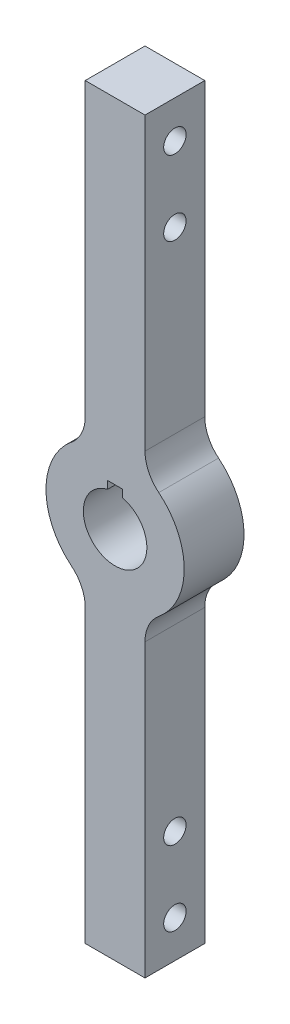
SolidWorks part; units mm, degrees
material "1060 Alloy"
ref_plane "Front Plane" through (0, 0, 0) normal (0, 0, 1) x (1, 0, 0)
ref_plane "Top Plane" through (0, 0, 0) normal (0, 1, 0) x (1, 0, 0)
ref_plane "Right Plane" through (0, 0, 0) normal (1, 0, 0) x (0, 0, -1)
sketch "Sketch1" plane through (0, 0, 0) normal (0, 0, 1) x (1, 0, 0)
  circle A0 centre (0, 0) radius 8.5
  circle A1 centre (0, 0) radius 18.5
  dimension "D1" = 17
  dimension "D2" = 37
extrude "Boss-Extrude1" add sketch "Sketch1" along normal mid plane 16
sketch "Sketch2" plane through (0, 0, 0) normal (0, 0, 1) x (1, 0, 0)
  line L0 (0, 0) -> (0, 40.1669) construction
  line L1 (-8, 100) -> (8, 100)
  line L2 (8, 100) -> (8, 16.6808)
  line L3 (8, 16.6808) -> (-8, 16.6808)
  line L4 (-8, 100) -> (-8, 16.6808)
  circle A0 centre (0, 0) radius 18.5 construction
  point P10 (0, 16.6808)
  point P11 (0, 100)
  dimension "D1" = 16
  dimension "D2" = 100
extrude "Boss-Extrude2" add sketch "Sketch2" along normal mid plane 16
sketch "Sketch3" plane through (0, 0, 0) normal (0, 0, 1) x (1, 0, 0)
  line L0 (0, 0) -> (0, -28.6568) construction
  line L1 (-8, -100) -> (8, -100)
  line L2 (8, -100) -> (8, -16.6808)
  line L3 (8, -16.6808) -> (-8, -16.6808)
  line L4 (-8, -100) -> (-8, -16.6808)
  arc A0 (-8, 16.6808) -> (8, 16.6808) centre (0, 0) ccw construction
  point P11 (0, -16.6808)
  point P12 (0, -100)
  dimension "D1" = 16
  dimension "D2" = 100
extrude "Boss-Extrude3" add sketch "Sketch3" along normal mid plane 16
sketch "Sketch4" plane through (0, 0, -8) normal (0, 0, -1) x (-1, 0, 0)
  line L0 (0, 0) -> (0, 24.3643) construction
  line L1 (2, 10.3) -> (-2, 10.3)
  line L2 (-2, 10.3) -> (-2, 8.2614)
  line L3 (-2, 8.2614) -> (2, 8.2614)
  line L4 (2, 10.3) -> (2, 8.2614)
  circle A0 centre (0, 0) radius 8.5 construction
  point P10 (0, 8.2614)
  point P11 (0, 10.3)
  dimension "D1" = 10.3
  dimension "D2" = 4
extrude "Cut-Extrude3" cut sketch "Sketch4" against normal through all
fillet "Fillet1" radius 10 4 edges at (8, -16.6808, 0) (-8, -16.6808, 0) (-8, 16.6808, 0) (8, 16.6808, 0)
sketch "Sketch5" plane through (8, 0, 0) normal (1, 0, 0) x (0, 0, -1)
  line L0 (0, 107.3318) -> (0, -108.104) construction
  line L1 (-8, 100) -> (8, 100) construction
  line L2 (-8, -100) -> (8, -100) construction
  circle A0 centre (0, 90) radius 3
  circle A1 centre (0, 70) radius 3
  circle A2 centre (0, -70) radius 3
  circle A3 centre (0, -90) radius 3
  dimension "D1" = 6
  dimension "D2" = 6
  dimension "D3" = 6
  dimension "D4" = 6
  dimension "D6" = 20
  dimension "D7" = 10
  dimension "D8" = 20
  dimension "D5" = 10
extrude "Cut-Extrude4" cut sketch "Sketch5" against normal through all
